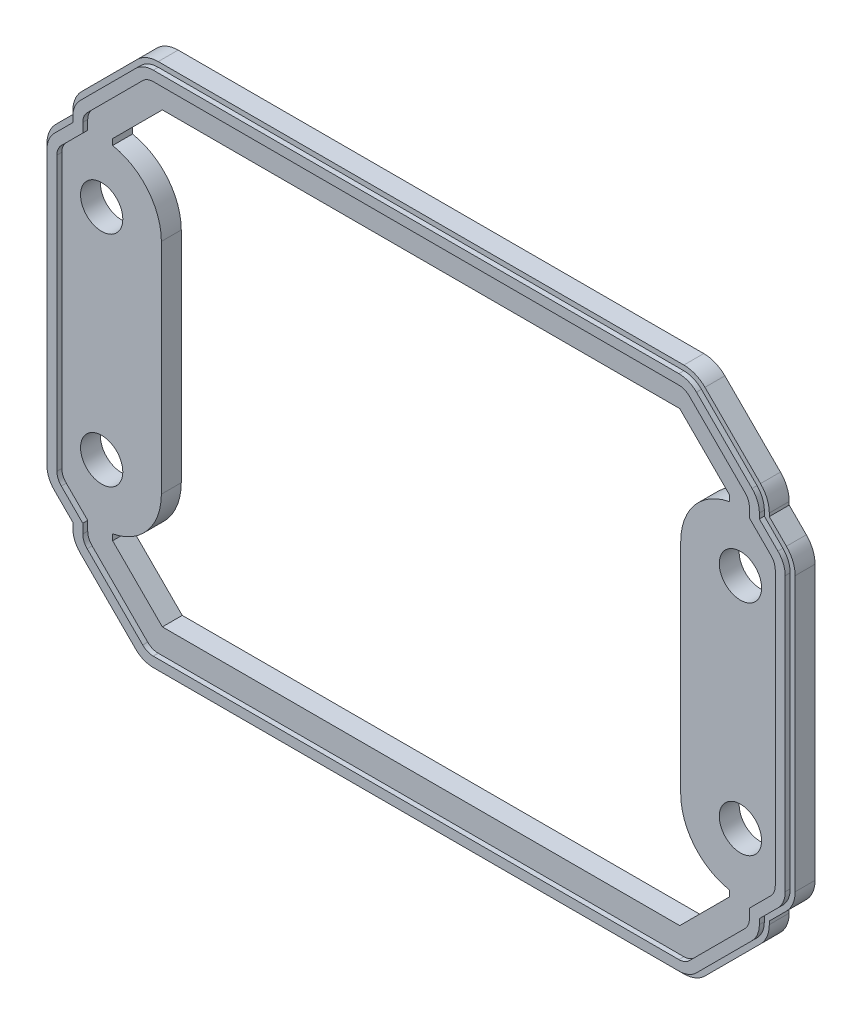
SolidWorks part; units mm, degrees
ref_plane "Front Plane" through (0, 0, 0) normal (0, 0, 1) x (1, 0, 0)
ref_plane "Top Plane" through (0, 0, 0) normal (0, 1, 0) x (1, 0, 0)
ref_plane "Right Plane" through (0, 0, 0) normal (1, 0, 0) x (0, 0, -1)
sketch "Sketch1" plane through (0, 0, 0) normal (0, 0, 1) x (1, 0, 0)
  line L12 (-1.6569, 49) -> (-53.6569, 49)
  line L13 (3.3431, 44) -> (-1.6569, 49)
  line L14 (3.3431, 43.3983) -> (3.3431, 44)
  line L15 (-1.5569, 15.5) -> (-1.5569, 37.5)
  line L16 (-64.3782, 10.6213) -> (-62.6569, 8.9)
  line L17 (-62.6569, 8.9) -> (-62.6569, 8.5858)
  line L18 (-61.7782, 6.4645) -> (-56.1924, 0.8787)
  line L19 (-54.0711, 0) -> (-1.2426, 0)
  line L20 (0.8787, 0.8787) -> (6.4645, 6.4645)
  line L21 (7.3431, 8.5858) -> (7.3431, 8.9)
  line L22 (7.3431, 8.9) -> (9.0645, 10.6213)
  line L23 (9.9431, 12.7426) -> (9.9431, 40.2574)
  line L24 (9.0645, 42.3787) -> (7.3431, 44.1)
  line L25 (7.3431, 44.1) -> (7.3431, 44.4142)
  line L26 (6.4645, 46.5355) -> (0.8787, 52.1213)
  line L27 (-1.2426, 53) -> (-54.0711, 53)
  line L28 (-56.1924, 52.1213) -> (-61.7782, 46.5355)
  line L29 (-62.6569, 44.4142) -> (-62.6569, 44.1)
  line L30 (-62.6569, 44.1) -> (-64.3782, 42.3787)
  line L31 (-65.2569, 40.2574) -> (-65.2569, 12.7426)
  line L32 (-64.3782, 10.6213) -> (-62.6569, 8.9)
  line L33 (-62.6569, 8.9) -> (-62.6569, 8.5858)
  line L34 (-61.7782, 6.4645) -> (-56.1924, 0.8787)
  line L35 (-54.0711, 0) -> (-1.2426, 0)
  line L36 (0.8787, 0.8787) -> (6.4645, 6.4645)
  line L37 (7.3431, 8.5858) -> (7.3431, 8.9)
  line L38 (7.3431, 8.9) -> (9.0645, 10.6213)
  line L39 (9.9431, 12.7426) -> (9.9431, 40.2574)
  line L40 (9.0645, 42.3787) -> (7.3431, 44.1)
  line L41 (7.3431, 44.1) -> (7.3431, 44.4142)
  line L42 (6.4645, 46.5355) -> (0.8787, 52.1213)
  line L43 (-1.2426, 53) -> (-54.0711, 53)
  line L44 (-56.1924, 52.1213) -> (-61.7782, 46.5355)
  line L45 (-62.6569, 44.4142) -> (-62.6569, 44.1)
  line L46 (-62.6569, 44.1) -> (-64.3782, 42.3787)
  line L47 (-65.2569, 40.2574) -> (-65.2569, 12.7426)
  line L48 (3.3431, 9) -> (3.3431, 9.6017)
  line L49 (-1.6569, 4) -> (3.3431, 9)
  line L50 (-53.6569, 4) -> (-1.6569, 4)
  line L51 (-58.6569, 9) -> (-53.6569, 4)
  line L52 (-58.6569, 9.6017) -> (-58.6569, 9)
  line L53 (-53.7569, 37.5) -> (-53.7569, 15.5)
  line L54 (-58.6569, 44) -> (-58.6569, 43.3983)
  line L55 (-53.6569, 49) -> (-58.6569, 44)
  line L56 (-1.6569, 49) -> (-53.6569, 49)
  line L57 (3.3431, 44) -> (-1.6569, 49)
  line L58 (3.3431, 43.3983) -> (3.3431, 44)
  line L59 (-1.5569, 15.5) -> (-1.5569, 37.5)
  line L60 (3.3431, 9) -> (3.3431, 9.6017)
  line L61 (-1.6569, 4) -> (3.3431, 9)
  line L62 (-53.6569, 4) -> (-1.6569, 4)
  line L63 (-58.6569, 9) -> (-53.6569, 4)
  line L64 (-58.6569, 9.6017) -> (-58.6569, 9)
  line L65 (-53.7569, 37.5) -> (-53.7569, 15.5)
  line L66 (-58.6569, 44) -> (-58.6569, 43.3983)
  line L67 (-53.6569, 49) -> (-58.6569, 44)
  circle A1 centre (4.4431, 37.5) radius 2.125
  circle A2 centre (4.4431, 37.5) radius 2.125
  circle A3 centre (-59.7569, 37.5) radius 2.125
  circle A4 centre (-59.7569, 37.5) radius 2.125
  circle A5 centre (-59.7569, 15.5) radius 2.125
  circle A6 centre (-59.7569, 15.5) radius 2.125
  circle A7 centre (4.4431, 15.5) radius 2.125
  circle A8 centre (4.4431, 15.5) radius 2.125
  arc A12 (3.3431, 43.3983) -> (-1.5569, 37.5) centre (4.4431, 37.5) ccw
  arc A13 (-1.5569, 15.5) -> (3.3431, 9.6017) centre (4.4431, 15.5) ccw
  arc A14 (-58.6569, 9.6017) -> (-53.7569, 15.5) centre (-59.7569, 15.5) ccw
  arc A15 (-53.7569, 37.5) -> (-58.6569, 43.3983) centre (-59.7569, 37.5) ccw
  arc A16 (3.3431, 43.3983) -> (-1.5569, 37.5) centre (4.4431, 37.5) ccw
  arc A17 (-1.5569, 15.5) -> (3.3431, 9.6017) centre (4.4431, 15.5) ccw
  arc A18 (-58.6569, 9.6017) -> (-53.7569, 15.5) centre (-59.7569, 15.5) ccw
  arc A19 (-53.7569, 37.5) -> (-58.6569, 43.3983) centre (-59.7569, 37.5) ccw
  arc A56 (9.0645, 10.6213) -> (9.9431, 12.7426) centre (6.9431, 12.7426) ccw
  arc A57 (9.0645, 10.6213) -> (9.9431, 12.7426) centre (6.9431, 12.7426) ccw
  arc A58 (9.9431, 40.2574) -> (9.0645, 42.3787) centre (6.9431, 40.2574) ccw
  arc A59 (9.9431, 40.2574) -> (9.0645, 42.3787) centre (6.9431, 40.2574) ccw
  arc A60 (7.3431, 44.4142) -> (6.4645, 46.5355) centre (4.3431, 44.4142) ccw
  arc A61 (7.3431, 44.4142) -> (6.4645, 46.5355) centre (4.3431, 44.4142) ccw
  arc A62 (0.8787, 52.1213) -> (-1.2426, 53) centre (-1.2426, 50) ccw
  arc A63 (0.8787, 52.1213) -> (-1.2426, 53) centre (-1.2426, 50) ccw
  arc A64 (-54.0711, 53) -> (-56.1924, 52.1213) centre (-54.0711, 50) ccw
  arc A65 (-54.0711, 53) -> (-56.1924, 52.1213) centre (-54.0711, 50) ccw
  arc A66 (-61.7782, 46.5355) -> (-62.6569, 44.4142) centre (-59.6569, 44.4142) ccw
  arc A67 (-61.7782, 46.5355) -> (-62.6569, 44.4142) centre (-59.6569, 44.4142) ccw
  arc A68 (-64.3782, 42.3787) -> (-65.2569, 40.2574) centre (-62.2569, 40.2574) ccw
  arc A69 (-64.3782, 42.3787) -> (-65.2569, 40.2574) centre (-62.2569, 40.2574) ccw
  arc A70 (-65.2569, 12.7426) -> (-64.3782, 10.6213) centre (-62.2569, 12.7426) ccw
  arc A71 (-65.2569, 12.7426) -> (-64.3782, 10.6213) centre (-62.2569, 12.7426) ccw
  arc A72 (-62.6569, 8.5858) -> (-61.7782, 6.4645) centre (-59.6569, 8.5858) ccw
  arc A73 (-62.6569, 8.5858) -> (-61.7782, 6.4645) centre (-59.6569, 8.5858) ccw
  arc A74 (-56.1924, 0.8787) -> (-54.0711, 0) centre (-54.0711, 3) ccw
  arc A75 (-56.1924, 0.8787) -> (-54.0711, 0) centre (-54.0711, 3) ccw
  arc A76 (-1.2426, 0) -> (0.8787, 0.8787) centre (-1.2426, 3) ccw
  arc A77 (-1.2426, 0) -> (0.8787, 0.8787) centre (-1.2426, 3) ccw
  arc A78 (6.4645, 6.4645) -> (7.3431, 8.5858) centre (4.3431, 8.5858) ccw
  arc A79 (6.4645, 6.4645) -> (7.3431, 8.5858) centre (4.3431, 8.5858) ccw
  dimension "D1" = 0
  dimension "D2" = 0
  dimension "D3" = 0
  dimension "D4" = 0
  dimension "D5" = 0
  dimension "D6" = 0
extrude "Boss-Extrude1" add sketch "Sketch1" along normal blind 2
sketch "Sketch2" plane through (0, 0, 2) normal (0, 0, 1) x (1, 0, 0)
  line L58 (-62.1569, 9.1071) -> (-62.1569, 8.5858)
  line L59 (-61.4246, 6.818) -> (-55.8388, 1.2322)
  line L60 (-54.0711, 0.5) -> (-1.2426, 0.5)
  line L61 (0.5251, 1.2322) -> (6.1109, 6.818)
  line L62 (6.8431, 8.5858) -> (6.8431, 9.1071)
  line L63 (6.8431, 9.1071) -> (8.7109, 10.9749)
  line L64 (9.4431, 12.7426) -> (9.4431, 40.2574)
  line L65 (8.7109, 42.0251) -> (6.8431, 43.8929)
  line L66 (6.8431, 43.8929) -> (6.8431, 44.4142)
  line L67 (6.1109, 46.182) -> (0.5251, 51.7678)
  line L68 (-1.2426, 52.5) -> (-54.0711, 52.5)
  line L69 (-55.8388, 51.7678) -> (-61.4246, 46.182)
  line L70 (-62.1569, 44.4142) -> (-62.1569, 43.8929)
  line L71 (-62.1569, 43.8929) -> (-64.0246, 42.0251)
  line L72 (-64.7569, 40.2574) -> (-64.7569, 12.7426)
  line L73 (-64.0246, 10.9749) -> (-62.1569, 9.1071)
  line L74 (-62.1569, 9.1071) -> (-62.1569, 8.5858)
  line L75 (-61.4246, 6.818) -> (-55.8388, 1.2322)
  line L76 (-54.0711, 0.5) -> (-1.2426, 0.5)
  line L77 (0.5251, 1.2322) -> (6.1109, 6.818)
  line L78 (6.8431, 8.5858) -> (6.8431, 9.1071)
  line L79 (6.8431, 9.1071) -> (8.7109, 10.9749)
  line L80 (9.4431, 12.7426) -> (9.4431, 40.2574)
  line L81 (8.7109, 42.0251) -> (6.8431, 43.8929)
  line L82 (6.8431, 43.8929) -> (6.8431, 44.4142)
  line L83 (6.1109, 46.182) -> (0.5251, 51.7678)
  line L84 (-1.2426, 52.5) -> (-54.0711, 52.5)
  line L85 (-55.8388, 51.7678) -> (-61.4246, 46.182)
  line L86 (-62.1569, 44.4142) -> (-62.1569, 43.8929)
  line L87 (-62.1569, 43.8929) -> (-64.0246, 42.0251)
  line L88 (-64.7569, 40.2574) -> (-64.7569, 12.7426)
  line L89 (-64.0246, 10.9749) -> (-62.1569, 9.1071)
  line L111 (-61.1569, 9.5213) -> (-61.1569, 8.5858)
  line L112 (-60.7175, 7.5251) -> (-55.1317, 1.9393)
  line L113 (-54.0711, 1.5) -> (-1.2426, 1.5)
  line L114 (-0.182, 1.9393) -> (5.4038, 7.5251)
  line L115 (5.8431, 8.5858) -> (5.8431, 9.5213)
  line L116 (5.8431, 9.5213) -> (8.0038, 11.682)
  line L117 (8.4431, 12.7426) -> (8.4431, 40.2574)
  line L118 (8.0038, 41.318) -> (5.8431, 43.4787)
  line L119 (5.8431, 43.4787) -> (5.8431, 44.4142)
  line L120 (5.4038, 45.4749) -> (-0.182, 51.0607)
  line L121 (-1.2426, 51.5) -> (-54.0711, 51.5)
  line L122 (-55.1317, 51.0607) -> (-60.7175, 45.4749)
  line L123 (-61.1569, 44.4142) -> (-61.1569, 43.4787)
  line L124 (-61.1569, 43.4787) -> (-63.3175, 41.318)
  line L125 (-63.7569, 40.2574) -> (-63.7569, 12.7426)
  line L126 (-63.3175, 11.682) -> (-61.1569, 9.5213)
  line L127 (-61.1569, 9.5213) -> (-61.1569, 8.5858)
  line L128 (-60.7175, 7.5251) -> (-55.1317, 1.9393)
  line L129 (-54.0711, 1.5) -> (-1.2426, 1.5)
  line L130 (-0.182, 1.9393) -> (5.4038, 7.5251)
  line L131 (5.8431, 8.5858) -> (5.8431, 9.5213)
  line L132 (5.8431, 9.5213) -> (8.0038, 11.682)
  line L133 (8.4431, 12.7426) -> (8.4431, 40.2574)
  line L134 (8.0038, 41.318) -> (5.8431, 43.4787)
  line L135 (5.8431, 43.4787) -> (5.8431, 44.4142)
  line L136 (5.4038, 45.4749) -> (-0.182, 51.0607)
  line L137 (-1.2426, 51.5) -> (-54.0711, 51.5)
  line L138 (-55.1317, 51.0607) -> (-60.7175, 45.4749)
  line L139 (-61.1569, 44.4142) -> (-61.1569, 43.4787)
  line L140 (-61.1569, 43.4787) -> (-63.3175, 41.318)
  line L141 (-63.7569, 40.2574) -> (-63.7569, 12.7426)
  line L142 (-63.3175, 11.682) -> (-61.1569, 9.5213)
  arc A30 (-62.1569, 8.5858) -> (-61.4246, 6.818) centre (-59.6569, 8.5858) ccw
  arc A31 (-55.8388, 1.2322) -> (-54.0711, 0.5) centre (-54.0711, 3) ccw
  arc A32 (-1.2426, 0.5) -> (0.5251, 1.2322) centre (-1.2426, 3) ccw
  arc A33 (6.1109, 6.818) -> (6.8431, 8.5858) centre (4.3431, 8.5858) ccw
  arc A34 (8.7109, 10.9749) -> (9.4431, 12.7426) centre (6.9431, 12.7426) ccw
  arc A35 (9.4431, 40.2574) -> (8.7109, 42.0251) centre (6.9431, 40.2574) ccw
  arc A36 (6.8431, 44.4142) -> (6.1109, 46.182) centre (4.3431, 44.4142) ccw
  arc A37 (0.5251, 51.7678) -> (-1.2426, 52.5) centre (-1.2426, 50) ccw
  arc A38 (-54.0711, 52.5) -> (-55.8388, 51.7678) centre (-54.0711, 50) ccw
  arc A39 (-61.4246, 46.182) -> (-62.1569, 44.4142) centre (-59.6569, 44.4142) ccw
  arc A40 (-64.0246, 42.0251) -> (-64.7569, 40.2574) centre (-62.2569, 40.2574) ccw
  arc A41 (-64.7569, 12.7426) -> (-64.0246, 10.9749) centre (-62.2569, 12.7426) ccw
  arc A42 (-62.1569, 8.5858) -> (-61.4246, 6.818) centre (-59.6569, 8.5858) ccw
  arc A43 (-55.8388, 1.2322) -> (-54.0711, 0.5) centre (-54.0711, 3) ccw
  arc A44 (-1.2426, 0.5) -> (0.5251, 1.2322) centre (-1.2426, 3) ccw
  arc A45 (6.1109, 6.818) -> (6.8431, 8.5858) centre (4.3431, 8.5858) ccw
  arc A46 (8.7109, 10.9749) -> (9.4431, 12.7426) centre (6.9431, 12.7426) ccw
  arc A47 (9.4431, 40.2574) -> (8.7109, 42.0251) centre (6.9431, 40.2574) ccw
  arc A48 (6.8431, 44.4142) -> (6.1109, 46.182) centre (4.3431, 44.4142) ccw
  arc A49 (0.5251, 51.7678) -> (-1.2426, 52.5) centre (-1.2426, 50) ccw
  arc A50 (-54.0711, 52.5) -> (-55.8388, 51.7678) centre (-54.0711, 50) ccw
  arc A51 (-61.4246, 46.182) -> (-62.1569, 44.4142) centre (-59.6569, 44.4142) ccw
  arc A52 (-64.0246, 42.0251) -> (-64.7569, 40.2574) centre (-62.2569, 40.2574) ccw
  arc A53 (-64.7569, 12.7426) -> (-64.0246, 10.9749) centre (-62.2569, 12.7426) ccw
  arc A69 (-61.1569, 8.5858) -> (-60.7175, 7.5251) centre (-59.6569, 8.5858) ccw
  arc A70 (-55.1317, 1.9393) -> (-54.0711, 1.5) centre (-54.0711, 3) ccw
  arc A71 (-1.2426, 1.5) -> (-0.182, 1.9393) centre (-1.2426, 3) ccw
  arc A72 (5.4038, 7.5251) -> (5.8431, 8.5858) centre (4.3431, 8.5858) ccw
  arc A73 (8.0038, 11.682) -> (8.4431, 12.7426) centre (6.9431, 12.7426) ccw
  arc A74 (8.4431, 40.2574) -> (8.0038, 41.318) centre (6.9431, 40.2574) ccw
  arc A75 (5.8431, 44.4142) -> (5.4038, 45.4749) centre (4.3431, 44.4142) ccw
  arc A76 (-0.182, 51.0607) -> (-1.2426, 51.5) centre (-1.2426, 50) ccw
  arc A77 (-54.0711, 51.5) -> (-55.1317, 51.0607) centre (-54.0711, 50) ccw
  arc A78 (-60.7175, 45.4749) -> (-61.1569, 44.4142) centre (-59.6569, 44.4142) ccw
  arc A79 (-63.3175, 41.318) -> (-63.7569, 40.2574) centre (-62.2569, 40.2574) ccw
  arc A80 (-63.7569, 12.7426) -> (-63.3175, 11.682) centre (-62.2569, 12.7426) ccw
  arc A81 (-61.1569, 8.5858) -> (-60.7175, 7.5251) centre (-59.6569, 8.5858) ccw
  arc A82 (-55.1317, 1.9393) -> (-54.0711, 1.5) centre (-54.0711, 3) ccw
  arc A83 (-1.2426, 1.5) -> (-0.182, 1.9393) centre (-1.2426, 3) ccw
  arc A84 (5.4038, 7.5251) -> (5.8431, 8.5858) centre (4.3431, 8.5858) ccw
  arc A85 (8.0038, 11.682) -> (8.4431, 12.7426) centre (6.9431, 12.7426) ccw
  arc A86 (8.4431, 40.2574) -> (8.0038, 41.318) centre (6.9431, 40.2574) ccw
  arc A87 (5.8431, 44.4142) -> (5.4038, 45.4749) centre (4.3431, 44.4142) ccw
  arc A88 (-0.182, 51.0607) -> (-1.2426, 51.5) centre (-1.2426, 50) ccw
  arc A89 (-54.0711, 51.5) -> (-55.1317, 51.0607) centre (-54.0711, 50) ccw
  arc A90 (-60.7175, 45.4749) -> (-61.1569, 44.4142) centre (-59.6569, 44.4142) ccw
  arc A91 (-63.3175, 41.318) -> (-63.7569, 40.2574) centre (-62.2569, 40.2574) ccw
  arc A92 (-63.7569, 12.7426) -> (-63.3175, 11.682) centre (-62.2569, 12.7426) ccw
  dimension "D1" = 0.5
  dimension "D2" = 1.5
extrude "Boss-Extrude2" add sketch "Sketch2" along normal blind 0.5
